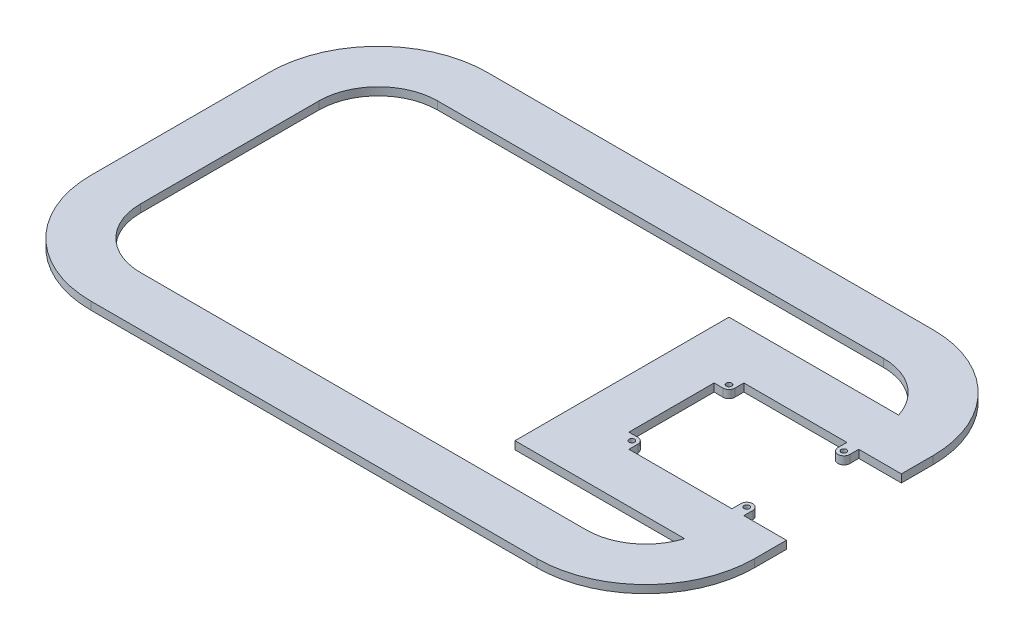
SolidWorks part; units mm, degrees
ref_plane "Front Plane" through (0, 0, 0) normal (0, 0, 1) x (1, 0, 0)
ref_plane "Top Plane" through (0, 0, 0) normal (0, 1, 0) x (1, 0, 0)
ref_plane "Right Plane" through (0, 0, 0) normal (1, 0, 0) x (0, 0, -1)
sketch "Sketch1" plane through (0, 0, 0) normal (0, 1, 0) x (1, 0, 0)
  line L0 (55, 25) -> (280, 25)
  line L1 (55, 0) -> (280, 0)
  line L2 (0, 55) -> (0, 145)
  line L3 (55, 200) -> (280, 200)
  line L4 (335, 145) -> (335, 129)
  line L5 (335, 55) -> (335, 71)
  line L6 (308.6182, 46) -> (308.6182, 46)
  line L7 (223, 46) -> (308.6182, 46)
  line L8 (335, 129) -> (313.5, 129)
  line L9 (223, 154) -> (223, 46)
  line L10 (308.6182, 154) -> (223, 154)
  line L11 (248, 121.5) -> (248, 78.5)
  line L12 (255.5, 71) -> (307.5, 71)
  line L13 (308.6182, 154) -> (308.6182, 154)
  line L14 (55, 175) -> (280, 175)
  line L15 (25, 55) -> (25, 145)
  line L16 (255.5, 124.5) -> (255.5, 129)
  line L17 (252.5, 121.5) -> (248, 121.5)
  line L18 (248, 129) -> (248, 71) construction
  line L19 (335, 129) -> (248, 129) construction
  line L20 (307.5, 124.5) -> (307.5, 129)
  line L21 (248, 100) -> (335, 100) construction
  line L22 (252.5, 78.5) -> (248, 78.5)
  line L23 (255.5, 75.5) -> (255.5, 71)
  line L24 (248, 71) -> (335, 71) construction
  line L25 (313.5, 124.5) -> (313.5, 129)
  line L26 (313.5, 75.5) -> (313.5, 71)
  line L27 (307.5, 75.5) -> (307.5, 71)
  line L28 (307.5, 129) -> (255.5, 129)
  line L29 (313.5, 71) -> (335, 71)
  arc A0 (55, 0) -> (0, 55) centre (55, 55) cw
  arc A1 (280, 0) -> (335, 55) centre (280, 55) ccw
  arc A2 (280, 200) -> (335, 145) centre (280, 145) cw
  arc A3 (0, 145) -> (55, 200) centre (55, 145) cw
  arc A4 (280, 25) -> (308.6182, 46) centre (280, 55) ccw
  arc A5 (280, 175) -> (308.6182, 154) centre (280, 145) cw
  arc A6 (25, 145) -> (55, 175) centre (55, 145) cw
  arc A7 (55, 25) -> (25, 55) centre (55, 55) cw
  circle A8 centre (252.5, 124.5) radius 1.375
  arc A9 (252.5, 121.5) -> (255.5, 124.5) centre (252.5, 124.5) ccw
  arc A10 (252.5, 78.5) -> (255.5, 75.5) centre (252.5, 75.5) cw
  circle A11 centre (252.5, 75.5) radius 1.375
  circle A12 centre (310.5, 124.5) radius 1.375
  arc A13 (307.5, 124.5) -> (313.5, 124.5) centre (310.5, 124.5) ccw
  arc A14 (307.5, 75.5) -> (313.5, 75.5) centre (310.5, 75.5) cw
  circle A15 centre (310.5, 75.5) radius 1.375
  point P7 (0, 0)
  point P15 (0, 200)
  point P28 (252.5, 124.5)
  point P43 (335, 137)
  point P45 (310.5, 124.5)
  dimension "D3" = 55
  dimension "D7" = 87
  dimension "D9" = 2.75
  dimension "D10" = 3
  dimension "D12" = 2.75
  dimension "D13" = 3
  dimension "D1" = 335
  dimension "D2" = 200
  dimension "D5" = 58
  dimension "D6" = 4.5
  dimension "D8" = 4.5
  dimension "D11" = 58
  dimension "D4" = 25
extrude "Boss-Extrude1" add sketch "Sketch1" along normal blind 4
sketch "Sketch2" plane through (0, 0, 0) normal (0, 1, 0) x (1, 0, 0)
  line L0 (313.5, 129) -> (335, 129) construction
  line L1 (249, 72) -> (334, 72)
  line L2 (249, 72) -> (249, 128)
  line L3 (249, 128) -> (334, 128)
  line L4 (334, 72) -> (334, 128)
  line L5 (248, 78.5) -> (248, 121.5) construction
  line L6 (281.5, 128) -> (281.5, 72) construction
  line L8 (291.5, 128) -> (291.5, 72) construction
  line L9 (249, 100) -> (334, 100) construction
  circle A0 centre (252.5, 124.5) radius 3
  circle A1 centre (252.5, 124.5) radius 1.375
  circle A2 centre (252.5, 75.5) radius 3
  circle A3 centre (252.5, 75.5) radius 1.375
  circle A4 centre (310.5, 124.5) radius 1.375
  circle A5 centre (310.5, 124.5) radius 3
  circle A6 centre (310.5, 75.5) radius 3
  circle A7 centre (310.5, 75.5) radius 1.375
  point P10 (252.5, 124.5)
  dimension "D7" = 29
  dimension "D8" = 2.75
  dimension "D9" = 6
  dimension "D1" = 85
  dimension "D2" = 56
  dimension "D3" = 1
  dimension "D4" = 1
  dimension "D5" = 3.5
  dimension "D6" = 3.5
